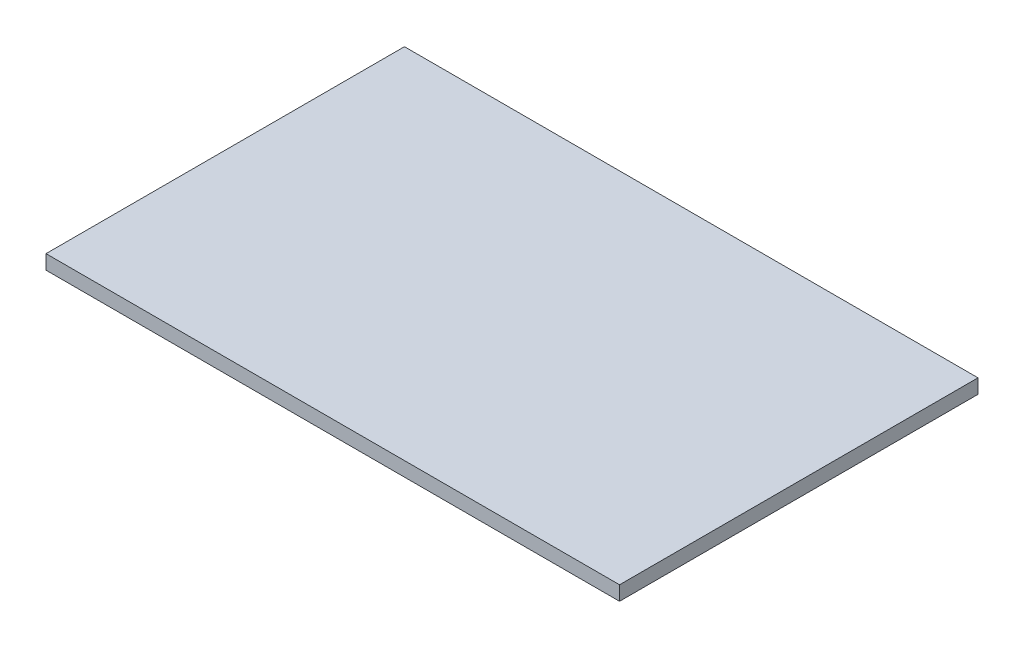
SolidWorks part; units mm, degrees
ref_plane "Front Plane" through (0, 0, 0) normal (0, 0, 1) x (1, 0, 0)
ref_plane "Top Plane" through (0, 0, 0) normal (0, 1, 0) x (1, 0, 0)
ref_plane "Right Plane" through (0, 0, 0) normal (1, 0, 0) x (0, 0, -1)
sketch "Sketch1" plane through (0, 0, 0) normal (0, 1, 0) x (1, 0, 0)
  line L1 (-200, 125) -> (200, 125)
  line L2 (-200, 125) -> (-200, -125)
  line L3 (-200, -125) -> (200, -125)
  line L4 (200, 125) -> (200, -125)
  line L5 (-200, 125) -> (200, -125) construction
  line L6 (-200, -125) -> (200, 125) construction
  point P0 (0, 0)
  dimension "D1" = 250
  dimension "D2" = 400
extrude "Boss-Extrude1" add sketch "Sketch1" along normal blind 10
